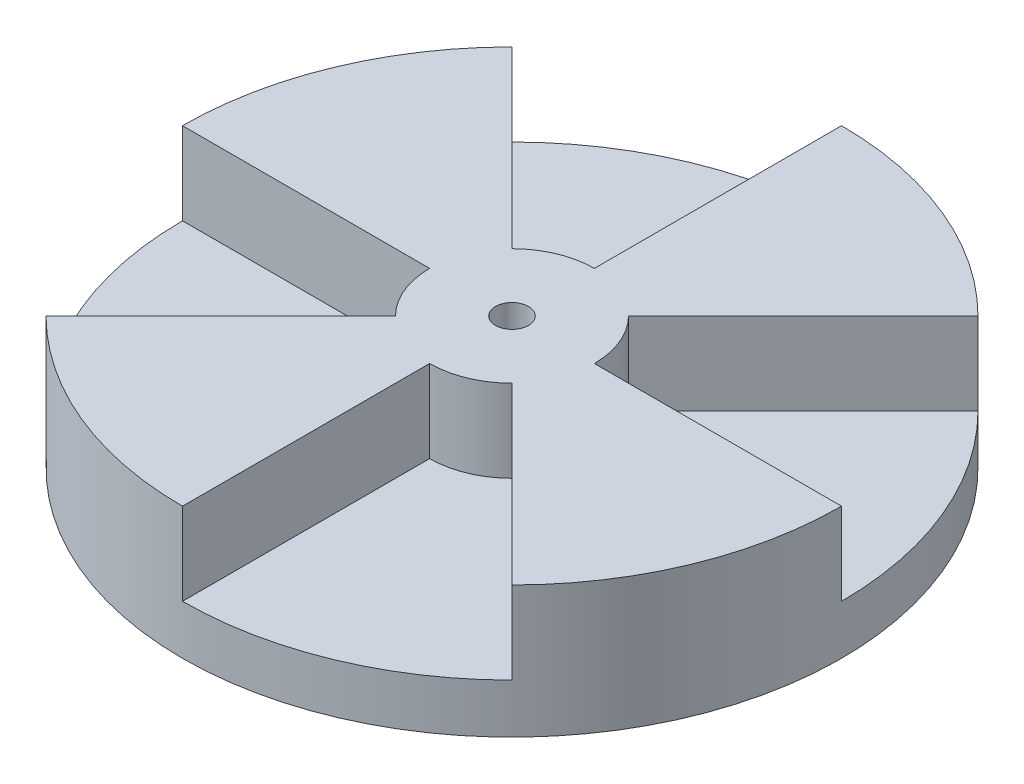
SolidWorks part; units mm, degrees
ref_plane "Front Plane" through (0, 0, 0) normal (0, 0, 1) x (1, 0, 0)
ref_plane "Top Plane" through (0, 0, 0) normal (0, 1, 0) x (1, 0, 0)
ref_plane "Right Plane" through (0, 0, 0) normal (1, 0, 0) x (0, 0, -1)
sketch "Sketch1" plane through (0, 0, 0) normal (0, 1, 0) x (1, 0, 0)
  circle A0 centre (0, 0) radius 20
  dimension "D1" = 40
extrude "Extrude (Mechanism Part 2)" add sketch "Sketch1" along normal blind 8
sketch "Sketch2" plane through (0, 8, 0) normal (0, 1, 0) x (1, 0, 0)
  line L0 (0, 0) -> (0, 20)
  line L1 (0, 0) -> (20, 0)
  line L2 (0, 0) -> (0, -20)
  line L3 (0, 0) -> (-20, 0)
  line L4 (0, 0) -> (14.1421, 14.1421)
  line L5 (0, 0) -> (14.1421, -14.1421)
  line L6 (0, 0) -> (-14.1421, -14.1421)
  line L7 (0, 0) -> (-14.1421, 14.1421)
  circle A0 centre (0, 0) radius 5
  circle A1 centre (0, 0) radius 20 construction
  circle M3 centre (0, 0) radius 20
  dimension "D1" = 10
  dimension "D2" = 135
extrude "Cut (Mechansim Part 2)" cut sketch "Sketch2" against normal blind 5 contours A0 L0 L7 M3 | A0 L3 L6 M3 | A0 L2 L5 M3 | A0 L1 L4 M3
sketch "Sketch3" plane through (0, 8, 0) normal (0, 1, 0) x (1, 0, 0)
  circle A0 centre (0, 0) radius 1
  dimension "D1" = 2
extrude "Hole for Screw (Mechansim Part 2)" cut sketch "Sketch3" against normal blind 10
